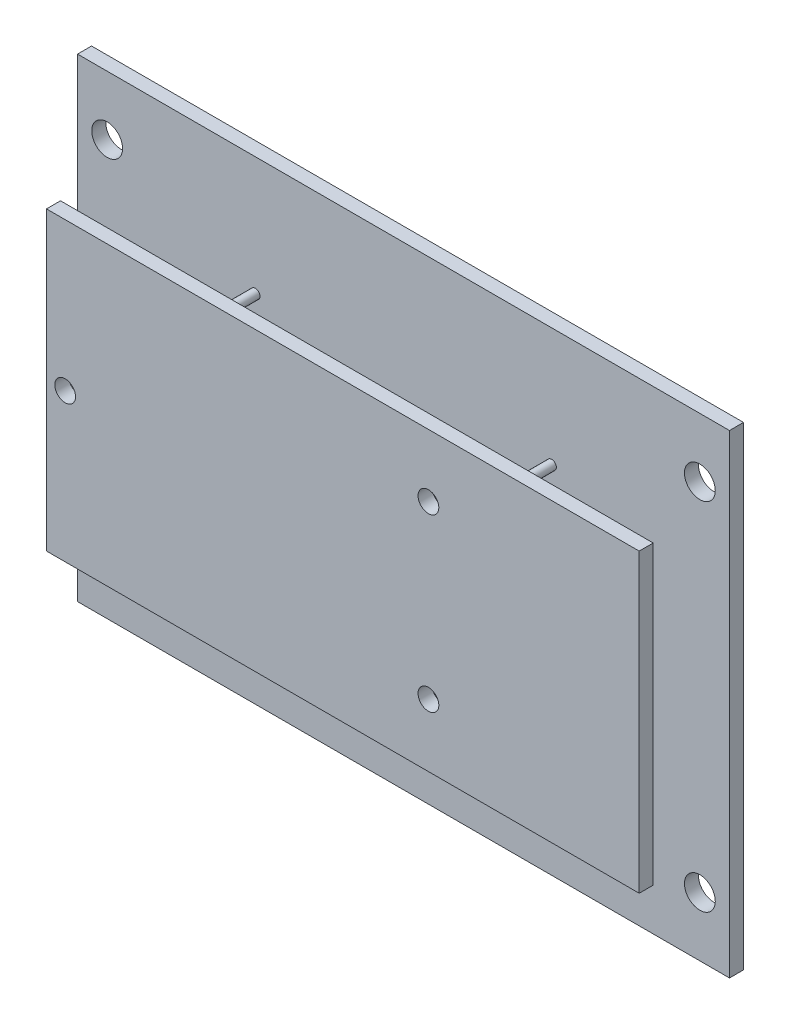
SolidWorks part; units mm, degrees
ref_plane "Front Plane" through (0, 0, 0) normal (0, 0, 1) x (1, 0, 0)
ref_plane "Top Plane" through (0, 0, 0) normal (0, 1, 0) x (1, 0, 0)
ref_plane "Right Plane" through (0, 0, 0) normal (1, 0, 0) x (0, 0, -1)
sketch "Sketch1" plane through (0, 0, 0) normal (0, 0, 1) x (1, 0, 0)
  line L1 (69.85, -50.8) -> (-69.85, -50.8)
  line L2 (69.85, -50.8) -> (69.85, 50.8)
  line L3 (69.85, 50.8) -> (-69.85, 50.8)
  line L4 (-69.85, -50.8) -> (-69.85, 50.8)
  line L5 (69.85, -50.8) -> (-69.85, 50.8) construction
  line L6 (69.85, 50.8) -> (-69.85, -50.8) construction
  line L8 (-76.2, -56.2) -> (-76.2, 56.2) construction
  point P0 (0, 0)
  point P5 (0, 0)
  point P7 (0, 0)
  point P8 (43.3319, 44.9096)
  point P11 (-38.1, -33.5153)
  point P12 (-38.1, -33.5153)
  point P13 (-38.1, -33.5153)
  point P14 (0, 0)
  point P15 (-39.1714, 38.46)
  point P16 (-38.1, 39.2303)
  point P17 (0, 0)
  dimension "D1" = 139.7
  dimension "D2" = 101.6
extrude "Boss-Extrude1" add sketch "Sketch1" along normal blind 3
sketch "Sketch2" plane through (0, 0, 3) normal (0, 0, 1) x (1, 0, 0)
  line L1 (-31.75, -25.4) -> (31.75, -25.4) construction
  line L2 (-31.75, -25.4) -> (-31.75, 25.4) construction
  line L3 (-31.75, 25.4) -> (31.75, 25.4) construction
  line L4 (31.75, -25.4) -> (31.75, 25.4) construction
  line L5 (-31.75, -25.4) -> (31.75, 25.4) construction
  line L6 (-31.75, 25.4) -> (31.75, -25.4) construction
  circle A0 centre (-31.75, 25.4) radius 1
  circle A1 centre (31.75, 25.4) radius 1
  circle A2 centre (31.75, -25.4) radius 1
  circle A3 centre (-31.75, -25.4) radius 1
  point P0 (0, 0)
  dimension "D2" = 2
  dimension "D1" = 63.5
  dimension "D3" = 50.8
extrude "Boss-Extrude2" add sketch "Sketch2" along normal blind 13
sketch "Sketch3" plane through (0, 0, 16) normal (0, 0, 1) x (1, 0, 0)
  line L1 (-63.5, -31.75) -> (63.5, -31.75)
  line L2 (-63.5, -31.75) -> (-63.5, 31.75)
  line L3 (-63.5, 31.75) -> (63.5, 31.75)
  line L4 (63.5, -31.75) -> (63.5, 31.75)
  line L5 (-63.5, -31.75) -> (63.5, 31.75) construction
  line L6 (-63.5, 31.75) -> (63.5, -31.75) construction
  point P0 (0, 0)
  dimension "D1" = 63.5
  dimension "D2" = 127
extrude "Boss-Extrude3" add sketch "Sketch3" against normal blind 3
sketch "Sketch4" plane through (0, 0, 3) normal (0, 0, 1) x (1, 0, 0)
  line L1 (-63.5, 38.1) -> (63.5, 38.1) construction
  line L2 (-63.5, 38.1) -> (-63.5, -38.1) construction
  line L3 (-63.5, -38.1) -> (63.5, -38.1) construction
  line L4 (63.5, 38.1) -> (63.5, -38.1) construction
  line L5 (-63.5, 38.1) -> (63.5, -38.1) construction
  line L6 (-63.5, -38.1) -> (63.5, 38.1) construction
  circle A0 centre (-63.5, -38.1) radius 3.302
  circle A1 centre (63.5, 38.1) radius 3.302
  circle A2 centre (-63.5, 38.1) radius 3.302
  circle A3 centre (63.5, -38.1) radius 3.302
  point P4 (0, 0)
  dimension "D3" = 6.604
  dimension "D1" = 76.2
  dimension "D2" = 127
extrude "Cut-Extrude1" cut sketch "Sketch4" against normal through all both and the other way through all
sketch "Sketch5" plane through (0, 0, 16) normal (0, 0, 1) x (1, 0, 0)
  line L2 (-59.5, 0) -> (0, 0) construction
  circle A0 centre (-59.5, 0) radius 2.2225
  circle A1 centre (18.3382, -18.3382) radius 2.2225
  circle A2 centre (18.3382, 18.3382) radius 2.2225
  point P2 (0, 0)
  point P6 (0, 0)
  point P7 (0, 0)
  point P8 (0, 0)
  point P11 (0, 0)
  point P13 (0, 0)
  point P14 (0, 0)
  point P16 (0, 0)
  dimension "D1" = 4.445
  dimension "D2" = 59.5
  dimension "D3" = 18.3382
  dimension "D4" = 18.3382
  dimension "D5" = 18.3382
extrude "Cut-Extrude2" cut sketch "Sketch5" against normal up to next and the other way through all
